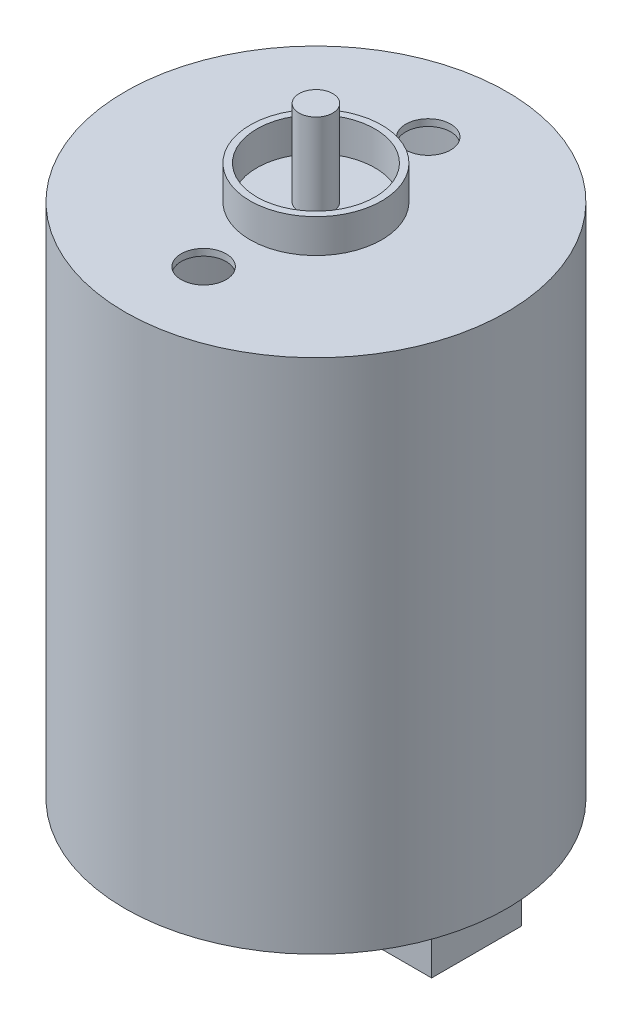
SolidWorks part; units mm, degrees
ref_plane "Front Plane" through (0, 0, 0) normal (0, 0, 1) x (1, 0, 0)
ref_plane "Top Plane" through (0, 0, 0) normal (0, 1, 0) x (1, 0, 0)
ref_plane "Right Plane" through (0, 0, 0) normal (1, 0, 0) x (0, 0, -1)
sketch "Sketch1" plane through (0, 0, 0) normal (0, 1, 0) x (1, 0, 0)
  circle A0 centre (0, 0) radius 8.5
extrude "Boss-Extrude1" add sketch "Sketch1" along normal blind 23
shell "Shell3" thickness 0.3
ref_plane "Plane2" through (0, 0.5, 0) normal (0, -1, 0) x (-1, 0, 0)
sketch "Sketch2" plane through (0, 0.5, 0) normal (0, -1, 0) x (-1, 0, 0)
  circle A0 centre (0, 0) radius 8.2
extrude "Boss-Extrude2" add sketch "Sketch2" against normal blind 0.3
sketch "Sketch3" plane through (0, 0.5, 0) normal (0, -1, 0) x (1, 0, 0)
  circle A0 centre (0, 0) radius 1.15
extrude "Boss-Extrude3" add sketch "Sketch3" along normal blind 1.5
sketch "Sketch4" plane through (0, 23, 0) normal (0, 1, 0) x (1, 0, 0)
  circle A0 centre (0, 0) radius 2.9296
  circle A1 centre (0, 0) radius 2.6296
  dimension "D1" = 0.3
extrude "Boss-Extrude4" add sketch "Sketch4" along normal blind 1.5
sketch "Sketch5" plane through (0, 23, 0) normal (0, 1, 0) x (1, 0, 0)
  circle A0 centre (0, 0) radius 0.75
  dimension "D1" = 1.5
extrude "Boss-Extrude5" add sketch "Sketch5" along normal blind 3.8
ref_plane "Plane3" through (0, 26.825, 0) normal (0, 1, 0) x (1, 0, 0)
sketch "Sketch7" plane through (0, 23, 0) normal (0, 1, 0) x (1, 0, 0)
  circle A0 centre (0, 5) radius 1
  circle A1 centre (0, -5) radius 1
  dimension "D3" = 2
  dimension "D4" = 2
  dimension "D1" = 5
  dimension "D2" = 5
extrude "Cut-Extrude1" cut sketch "Sketch7" against normal up to next
sketch "Sketch8" plane through (0, 0.5, 0) normal (0, -1, 0) x (1, 0, 0)
  line L1 (-7.15, 2) -> (-4.85, 2)
  line L2 (-7.15, 2) -> (-7.15, -2)
  line L3 (-7.15, -2) -> (-4.85, -2)
  line L4 (-4.85, 2) -> (-4.85, -2)
  line L5 (-7.15, 2) -> (-4.85, -2) construction
  line L6 (-7.15, -2) -> (-4.85, 2) construction
  line L7 (4.85, 2) -> (7.15, 2)
  line L8 (4.85, 2) -> (4.85, -2)
  line L9 (4.85, -2) -> (7.15, -2)
  line L10 (7.15, 2) -> (7.15, -2)
  line L11 (4.85, 2) -> (7.15, -2) construction
  line L12 (4.85, -2) -> (7.15, 2) construction
  point P0 (-6, 0)
  point P5 (6, 0)
  dimension "D1" = 4
  dimension "D2" = 2.3
  dimension "D3" = 4
  dimension "D4" = 2.3
  dimension "D5" = 6
  dimension "D6" = 6
  dimension "D7" = 0
  dimension "D8" = 0
extrude "Boss-Extrude7" add sketch "Sketch8" along normal blind 2.85
